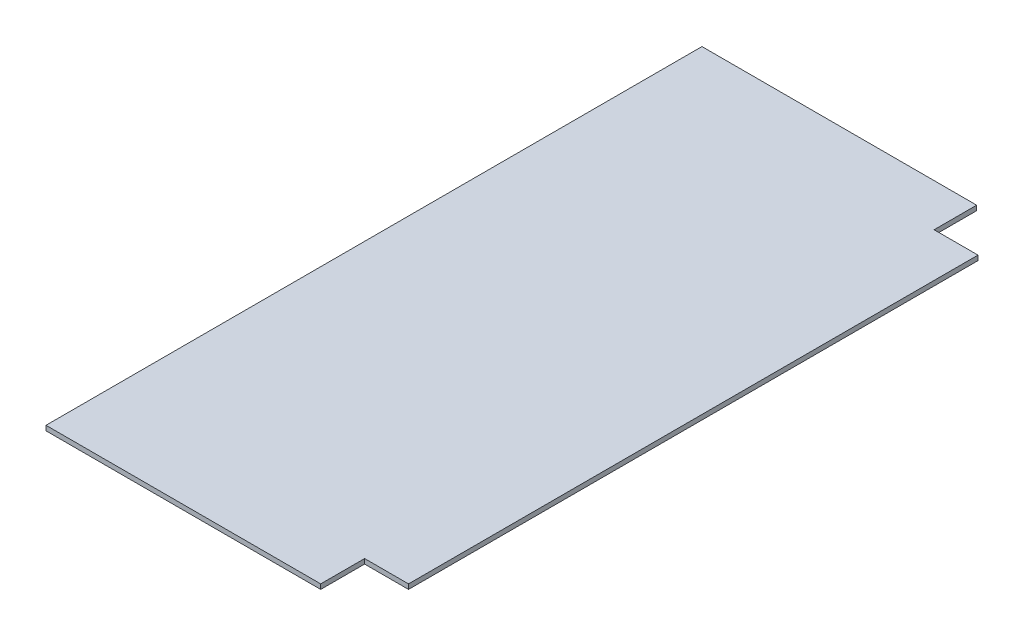
SolidWorks part; units mm, degrees
ref_plane "Front Plane" through (0, 0, 0) normal (0, 0, 1) x (1, 0, 0)
ref_plane "Top Plane" through (0, 0, 0) normal (0, 1, 0) x (1, 0, 0)
ref_plane "Right Plane" through (0, 0, 0) normal (1, 0, 0) x (0, 0, -1)
sketch "Sketch1" plane through (0, 0, 0) normal (0, 1, 0) x (1, 0, 0)
  line L5 (-304.5, -612.5) -> (304.5, -612.5)
  line L6 (-304.5, -612.5) -> (-304.5, 612.5)
  line L7 (-304.5, 612.5) -> (304.5, 612.5)
  line L14 (304.5, -612.5) -> (304.5, 612.5)
  line L15 (-304.5, -612.5) -> (304.5, 612.5) construction
  line L16 (-304.5, 612.5) -> (304.5, -612.5) construction
  line L17 (304.5, 612.5) -> (224.5, 612.5)
  line L18 (304.5, 612.5) -> (304.5, 497.5)
  line L21 (-304.5, 612.5) -> (-845.5, 612.5)
  line L22 (-304.5, 612.5) -> (-304.5, 497.5)
  line L26 (-304.5, -532.5) -> (-304.5, -612.5)
  line L27 (-304.5, -612.5) -> (-845.5, -612.5)
  line L29 (304.5, -612.5) -> (224.5, -612.5)
  line L30 (304.5, -612.5) -> (304.5, -532.5)
  point P0 (0, 0)
  point P1 (0, 0)
  point P5 (0, 0)
  point P9 (0, 0)
  dimension "D1" = 609
  dimension "D2" = 1225
extrude "Boss-Extrude1" add sketch "Sketch1" along normal blind 9
sketch "Sketch2" plane through (0, 9, 0) normal (0, 1, 0) x (1, 0, 0)
  line L0 (-290.5, 612.5) -> (-290.5, -612.5) construction
  line L1 (-290.5, 612.5) -> (-290.5, -612.5)
  line L2 (-290.5, -612.5) -> (-304.5, -612.5)
  line L3 (-304.5, 612.5) -> (-290.5, 612.5)
  line L7 (-304.5, -612.5) -> (304.5, -612.5)
  line L8 (304.5, -612.5) -> (304.5, 612.5)
  line L9 (304.5, 612.5) -> (-304.5, 612.5)
  line L10 (-304.5, 612.5) -> (-304.5, -612.5)
  line L11 (-304.5, -612.5) -> (304.5, -612.5)
  line L12 (304.5, -612.5) -> (304.5, 612.5)
  line L13 (304.5, 612.5) -> (-304.5, 612.5)
  line L14 (-304.5, 612.5) -> (-304.5, -612.5)
  line M8 (-304.5, -612.5) -> (304.5, -612.5)
  line M10 (304.5, 612.5) -> (-304.5, 612.5)
  line M11 (-304.5, 612.5) -> (-304.5, -612.5)
  dimension "D1" = 0
extrude "Cut-Extrude1" cut sketch "Sketch2" against normal blind 10 contours L1 M10 M11 M8
sketch "Sketch3" plane through (0, 9, 0) normal (0, 1, 0) x (1, 0, 0)
  line L0 (222.5, -612.5) -> (222.5, -530.5)
  line L1 (-290.5, -612.5) -> (304.5, -612.5) construction
  line L2 (222.5, -530.5) -> (304.5, -530.5)
  line L3 (304.5, -612.5) -> (304.5, 612.5) construction
  line L4 (304.5, 533) -> (222.5, 533)
  line L5 (222.5, 533) -> (222.5, 615)
  line L6 (264.5, 615) -> (-845.5, 615) construction
  line L7 (304.5, 533) -> (304.5, 612.5)
  line L8 (304.5, 612.5) -> (222.5, 615)
  line L9 (222.5, -612.5) -> (304.5, -612.5)
  line L10 (304.5, -612.5) -> (304.5, -530.5)
  dimension "D1" = 82
  dimension "D2" = 82
  dimension "D3" = 82
  dimension "D4" = 82
extrude "Cut-Extrude2" cut sketch "Sketch3" against normal blind 10
